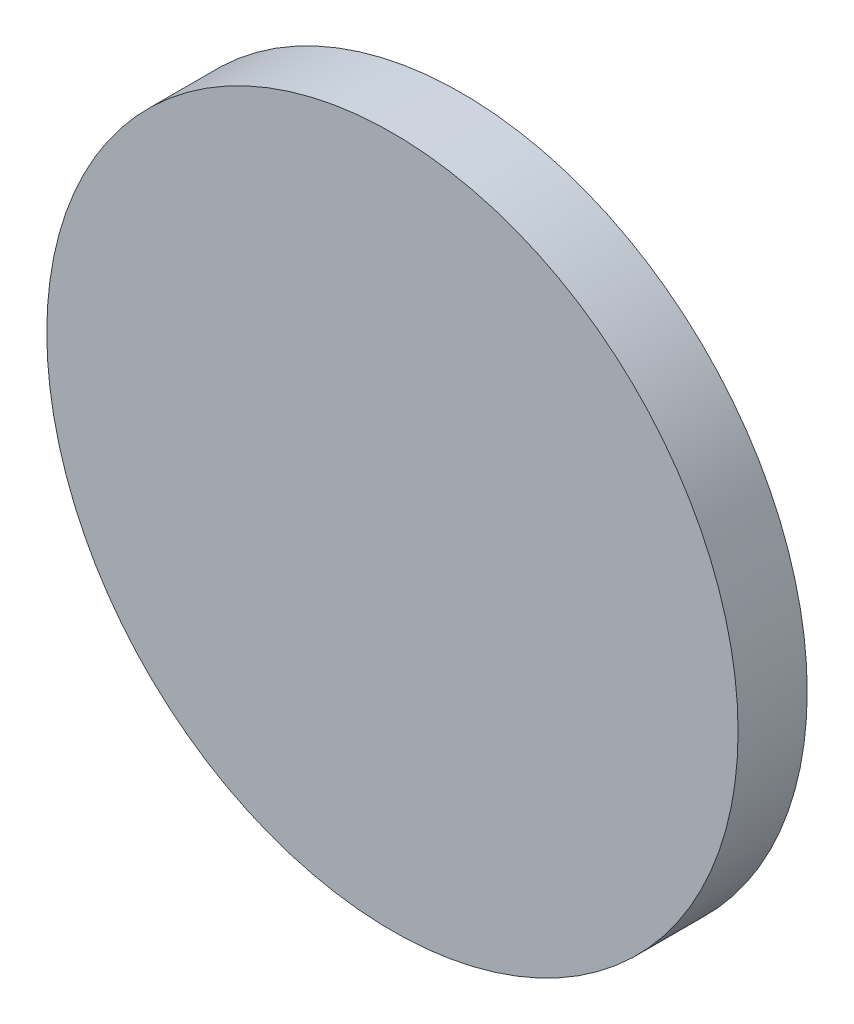
SolidWorks part; units mm, degrees
material "BUTYL"
ref_plane "Front Plane" through (0, 0, 0) normal (0, 0, 1) x (1, 0, 0)
ref_plane "Top Plane" through (0, 0, 0) normal (0, 1, 0) x (1, 0, 0)
ref_plane "Right Plane" through (0, 0, 0) normal (1, 0, 0) x (0, 0, -1)
sketch "Sketch1" plane through (0, 0, 0) normal (0, 0, 1) x (1, 0, 0)
  circle A0 centre (-181.5, -45.5) radius 2.5
  dimension "D1" = 5
extrude "Boss-Extrude1" add sketch "Sketch1" along normal blind 0.5
